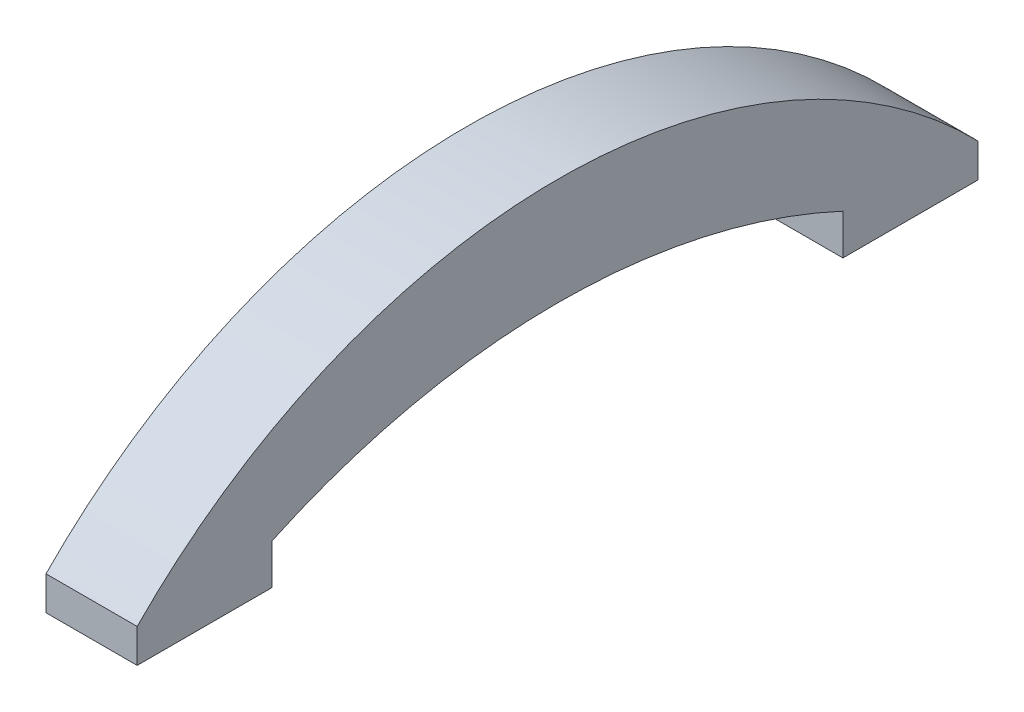
SolidWorks part; units mm, degrees
material "ABS PC"
ref_plane "Front Plane" through (0, 0, 0) normal (0, 0, 1) x (1, 0, 0)
ref_plane "Top Plane" through (0, 0, 0) normal (0, 1, 0) x (1, 0, 0)
ref_plane "Right Plane" through (0, 0, 0) normal (1, 0, 0) x (0, 0, -1)
sketch "Sketch1" plane through (0, 0, 0) normal (1, 0, 0) x (0, 0, -1)
  line L0 (0, 105.8598) -> (0, -242.7586) construction
  line L1 (-124.5, 0) -> (-84.5, 0)
  line L2 (-124.5, 0) -> (-124.5, 10)
  line L4 (-84.5, 0) -> (-84.5, 12)
  line L6 (84.5, 12) -> (84.5, 0)
  line L7 (84.5, 0) -> (124.5, 0)
  line L8 (124.5, 10) -> (124.5, 0)
  line L9 (-165.9142, 0) -> (199.8315, 0) construction
  arc A1 (-84.5, 12) -> (84.5, 12) centre (0, -169.2726) cw
  arc A2 (-124.5, 10) -> (124.5, 10) centre (0, -111.6266) cw
  point P11 (0, -111)
  dimension "D8" = 200
  dimension "D1" = 40
  dimension "D2" = 40
  dimension "D3" = 249
  dimension "D5" = 10
  dimension "D6" = 10
  dimension "D9" = 12
  dimension "D10" = 12
extrude "Boss-Extrude1" add sketch "Sketch1" along normal blind 27
sketch "Sketch3" plane through (0, 0, 0) normal (0, -1, 0) x (1, 0, 0)
  line L0 (27, 124.5) -> (27, 84.5) construction
  line L1 (1.75, 85.73) -> (25.25, 85.73)
  line L2 (1.75, 85.73) -> (1.75, 120.23)
  line L3 (1.75, 120.23) -> (25.25, 120.23)
  line L4 (25.25, 85.73) -> (25.25, 120.23)
  line L5 (0, 124.5) -> (0, 84.5) construction
  line L10 (27, -84.5) -> (27, -124.5) construction
  line L11 (1.75, -121.75) -> (25.25, -121.75)
  line L12 (1.75, -121.75) -> (1.75, -87.25)
  line L13 (1.75, -87.25) -> (25.25, -87.25)
  line L14 (25.25, -121.75) -> (25.25, -87.25)
  line L17 (0, -84.5) -> (0, -124.5) construction
  line L18 (27, -124.5) -> (0, -124.5) construction
  line L20 (27, -84.5) -> (0, -84.5) construction
  line L23 (27, 124.5) -> (0, 124.5) construction
  dimension "D1" = 34.5
  dimension "D2" = 34.5
  dimension "D3" = 23.5
  dimension "D4" = 1.75
  dimension "D5" = 1.75
  dimension "D6" = 4.27
  dimension "D7" = 23.5
  dimension "D8" = 34.5
  dimension "D9" = 34.5
  dimension "D10" = 23.5
  dimension "D11" = 23.5
  dimension "D12" = 1.75
  dimension "D13" = 23.5
  dimension "D14" = 2.75
  dimension "D15" = 1.75
  dimension "D16" = 2.75
extrude "Cut-Extrude1" cut sketch "Sketch3" against normal blind 7.5 contours L12 L11 L14 L13 | L2 L1 L4 L3
